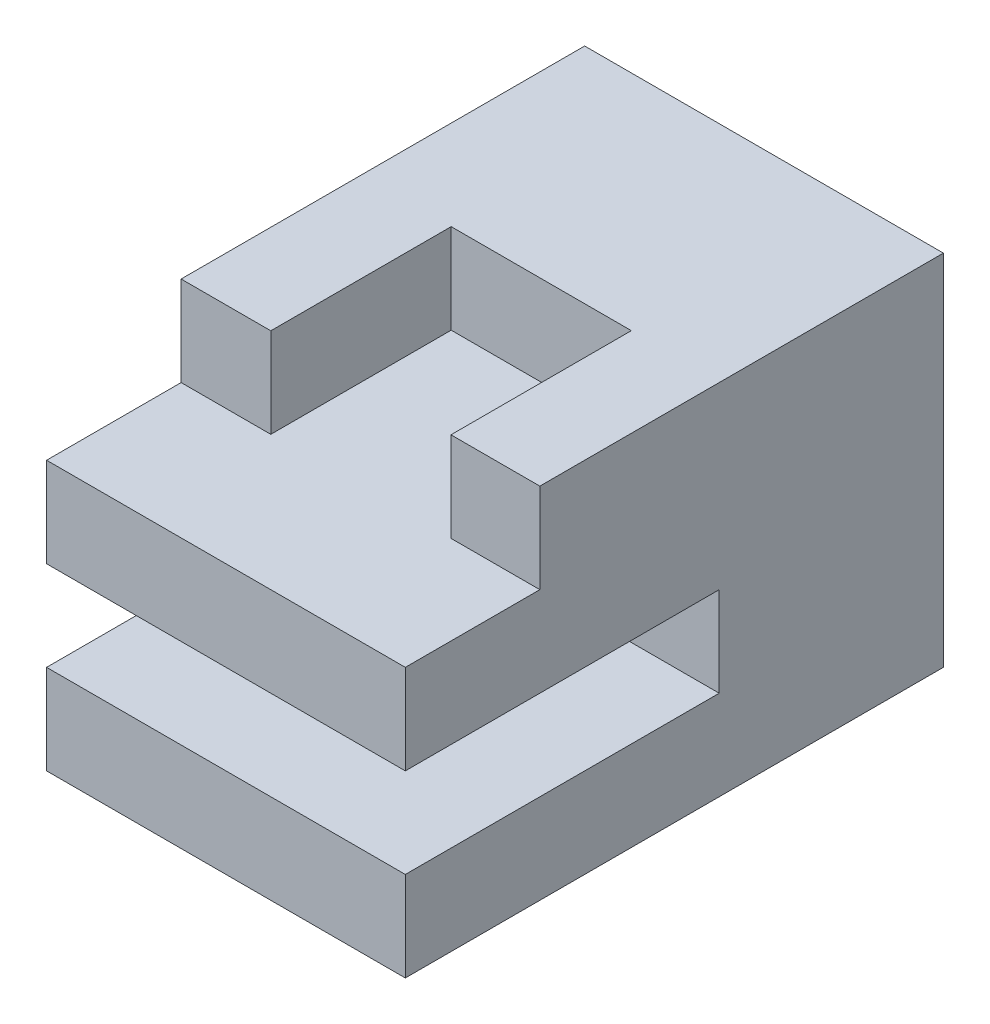
SolidWorks part; units mm, degrees
ref_plane "Front Plane" through (0, 0, 0) normal (0, 0, 1) x (1, 0, 0)
ref_plane "Top Plane" through (0, 0, 0) normal (0, 1, 0) x (1, 0, 0)
ref_plane "Right Plane" through (0, 0, 0) normal (1, 0, 0) x (0, 0, -1)
sketch "Sketch1" plane through (0, 0, 0) normal (0, 0, 1) x (1, 0, 0)
  line L1 (0, 0) -> (40, 0)
  line L2 (0, 0) -> (0, 40)
  line L3 (0, 40) -> (40, 40)
  line L4 (40, 0) -> (40, 40)
extrude "Boss-Extrude1" add sketch "Sketch1" along normal blind 60
sketch "Sketch2" plane through (0, 0, 60) normal (0, 0, 1) x (1, 0, 0)
  line L0 (40, 0) -> (40, 40) construction
  line L3 (0, 10) -> (40, 10)
  line L7 (0, 10) -> (0, 20)
  line L8 (0, 20) -> (40, 20)
  line L9 (40, 10) -> (40, 20)
extrude "Cut-Extrude1" cut sketch "Sketch2" against normal blind 35
sketch "Sketch3" plane through (0, 0, 60) normal (0, 0, 1) x (1, 0, 0)
  line L0 (40, 20) -> (40, 40) construction
  line L1 (0, 40) -> (40, 40)
  line L2 (0, 40) -> (0, 30)
  line L3 (0, 30) -> (40, 30)
  line L4 (40, 40) -> (40, 30)
extrude "Cut-Extrude2" cut sketch "Sketch3" against normal blind 15
sketch "Sketch4" plane through (0, 40, 0) normal (0, 1, 0) x (1, 0, 0)
  line L1 (10, -45) -> (30.0892, -45)
  line L11 (10, -45) -> (10, -24.8859)
  line L12 (10, -24.8859) -> (30.0892, -24.8859)
  line L13 (30.0892, -45) -> (30.0892, -24.8859)
extrude "Cut-Extrude3" cut sketch "Sketch4" against normal blind 10
